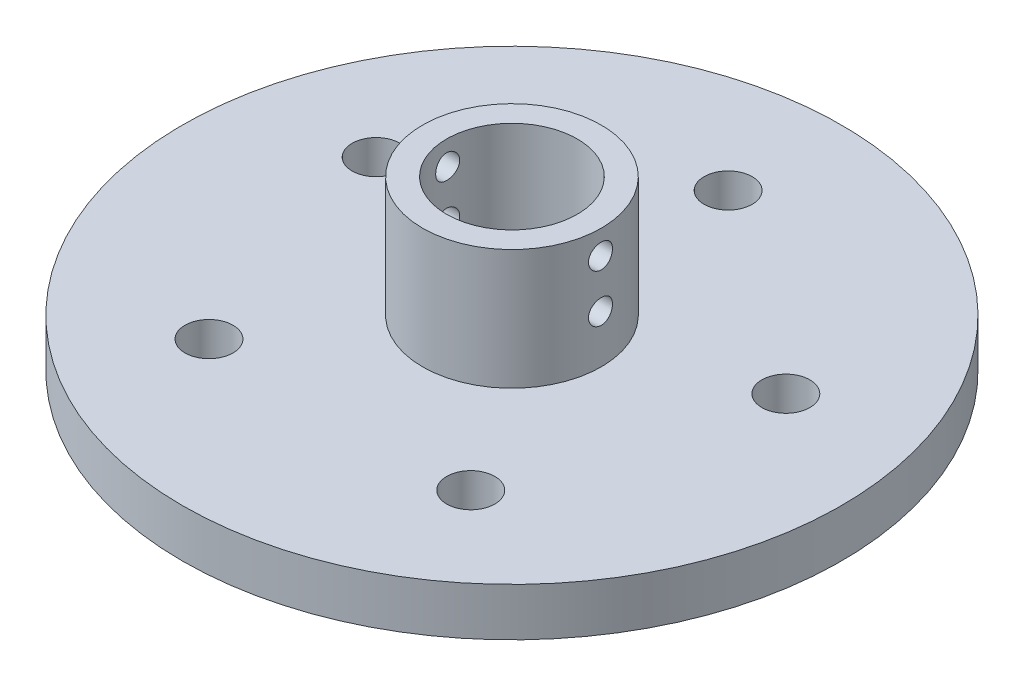
SolidWorks part; units mm, degrees
material "Delrin 2700 NC010, Low Viscosity Acetal Copolymer (SS)"
ref_plane "Front Plane" through (0, 0, 0) normal (0, 0, 1) x (1, 0, 0)
ref_plane "Top Plane" through (0, 0, 0) normal (0, 1, 0) x (1, 0, 0)
ref_plane "Right Plane" through (0, 0, 0) normal (1, 0, 0) x (0, 0, -1)
sketch "Sketch1" plane through (0, 0, 0) normal (0, 0, 1) x (1, 0, 0)
  line L0 (0, 7.8095) -> (0, 0) construction
  line L1 (0, 0) -> (17.272, 0) construction
  line L3 (17.272, 0) -> (87.122, 0)
  line L4 (17.272, 0) -> (17.272, 12.7)
  line L5 (17.272, 12.7) -> (87.122, 12.7)
  line L6 (87.122, 0) -> (87.122, 12.7)
  line L7 (17.272, 12.7) -> (23.622, 12.7)
  line L8 (17.272, 12.7) -> (17.272, 44.45)
  line L9 (17.272, 44.45) -> (23.622, 44.45)
  line L10 (23.622, 12.7) -> (23.622, 44.45)
  dimension "D1" = 17.272
  dimension "D2" = 12.7
  dimension "D3" = 6.35
  dimension "D4" = 31.75
  dimension "5.5" = 69.85
revolve "Revolve1" add sketch "Sketch1" angle 360 about L0
sketch "Sketch2" plane through (0, 12.7, 0) normal (0, 1, 0) x (1, 0, 0)
  line L0 (0, 57.15) -> (54.1556, 18.2562) construction
  line L1 (54.1556, 18.2562) -> (34.5994, -45.4863) construction
  line L2 (34.5994, -45.4863) -> (-34.5994, -45.4863) construction
  line L3 (-34.5994, -45.4863) -> (-54.1556, 18.2562) construction
  line L4 (-54.1556, 18.2562) -> (0, 57.15) construction
  circle A0 centre (0, 0) radius 57.15 construction
  point P3 (-54.1556, 18.2562)
  point P4 (0, 57.15)
  point P5 (54.1556, 18.2562)
  point P6 (-34.5994, -45.4863)
  point P7 (34.5994, -45.4863)
  dimension "D1" = 114.3
  dimension "D2" = 66.675
hole_wizard "1/2-20 Tapped Hole1" positions "Sketch3" profile "Sketch4" tap size "1/2-20" standard "ANSI Inch" end condition through all
sketch "Sketch3" plane through (0, 12.7, 0) normal (0, 1, 0) x (1, 0, 0)
  point P0 (-54.1556, 18.2562)
  point P3 (0, 57.15)
  point P6 (54.1556, 18.2562)
  point P9 (34.5994, -45.4863)
  point P12 (-34.5994, -45.4863)
sketch "Sketch4" plane through (-54.1556, 12.7, -18.2562) normal (1, 0, 0) x (0, 0, 1)
  line L0 (0, 0) -> (0, 12.7)
  line L1 (0, 12.7) -> (6.35, 12.7)
  line L2 (6.35, 12.7) -> (6.35, 0)
  line L5 (6.35, 0) -> (0, 0)
  line L11 (0, -6.35) -> (0, 107.95) construction
  dimension "Thru Tap Drill Dia." = 12.7
  dimension "Thru Tap Drill Depth" = 12.7
cosmetic thread "Hole Thread1" parameters "D2"=12.7
cosmetic thread "Hole Thread2" parameters "D2"=12.7
cosmetic thread "Hole Thread3" parameters "D2"=12.7
cosmetic thread "Hole Thread4" parameters "D2"=12.7
cosmetic thread "Hole Thread5" parameters "D2"=12.7
hole_wizard "1/4 (0.25) Diameter Hole1" positions "Sketch6" profile "Sketch7" hole size "1/4" standard "ANSI Inch"
sketch "Sketch6" plane through (0, 0, 0) normal (1, 0, 0) x (0, 0, -1)
  point P0 (0, 38.1)
  point P5 (0, 25.4)
  dimension "D1" = 38.1
  dimension "D2" = 25.4
sketch "Sketch7" plane through (0, 38.1, 0) normal (0, 1, 0) x (0, 0, 1)
  line L0 (0, 0) -> (0, 87.122)
  line L1 (0, 87.122) -> (3.175, 87.122)
  line L2 (3.175, 87.122) -> (3.175, 0)
  line L5 (3.175, 0) -> (0, 0)
  line L11 (0, -6.35) -> (0, 107.95) construction
  dimension "Thru Hole Dia." = 6.35
  dimension "Thru Hole Depth" = 87.122
hole_wizard "1/4 (0.25) Diameter Hole2" positions "Sketch8" profile "Sketch9" hole size "1/4" standard "ANSI Inch" end condition through all
sketch "Sketch8" plane through (0, 0, 0) normal (1, 0, 0) x (0, 0, -1)
  point P3 (0, 38.1)
  point P6 (0, 25.4)
  point P10 (0, 0)
sketch "Sketch9" plane through (0, 38.1, 0) normal (0, 1, 0) x (0, 0, -1)
  line L0 (0, 0) -> (0, 87.122)
  line L1 (0, 87.122) -> (3.175, 87.122)
  line L2 (3.175, 87.122) -> (3.175, 0)
  line L5 (3.175, 0) -> (0, 0)
  line L11 (0, -6.35) -> (0, 107.95) construction
  dimension "Thru Hole Dia." = 6.35
  dimension "Thru Hole Depth" = 87.122
